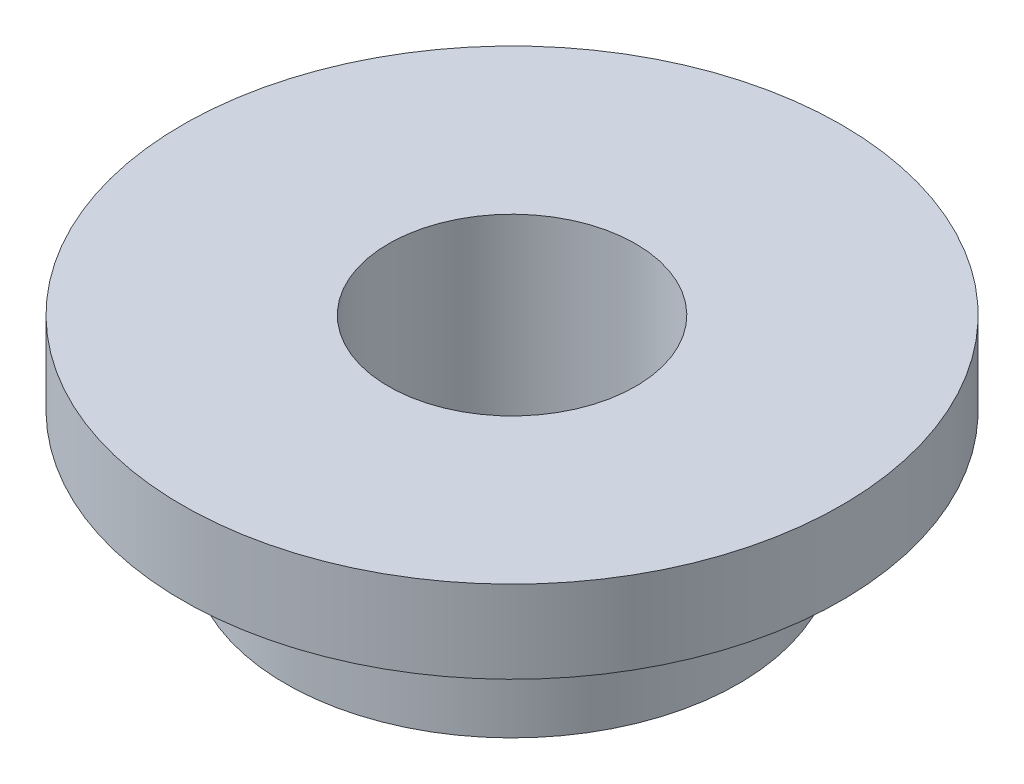
SolidWorks part; units mm, degrees
material "Aluminum Bronze"
ref_plane "Front Plane" through (0, 0, 0) normal (0, 0, 1) x (1, 0, 0)
ref_plane "Top Plane" through (0, 0, 0) normal (0, 1, 0) x (1, 0, 0)
ref_plane "Right Plane" through (0, 0, 0) normal (1, 0, 0) x (0, 0, -1)
sketch "Sketch1" plane through (0, 0, 0) normal (1, 0, 0) x (0, 0, -1)
  line L0 (0, 0) -> (0, 17.7571) construction
  line L1 (6, 0) -> (6, 10)
  line L2 (6, 10) -> (16, 10)
  line L3 (16, 10) -> (16, 6)
  line L4 (16, 6) -> (11, 6)
  line L5 (11, 6) -> (11, 0)
  line L6 (11, 0) -> (6, 0)
  dimension "D1" = 22
  dimension "D2" = 32
  dimension "D3" = 12
  dimension "D4" = 10
  dimension "D5" = 4
revolve "Revolve1" add sketch "Sketch1" angle 360 about L0
